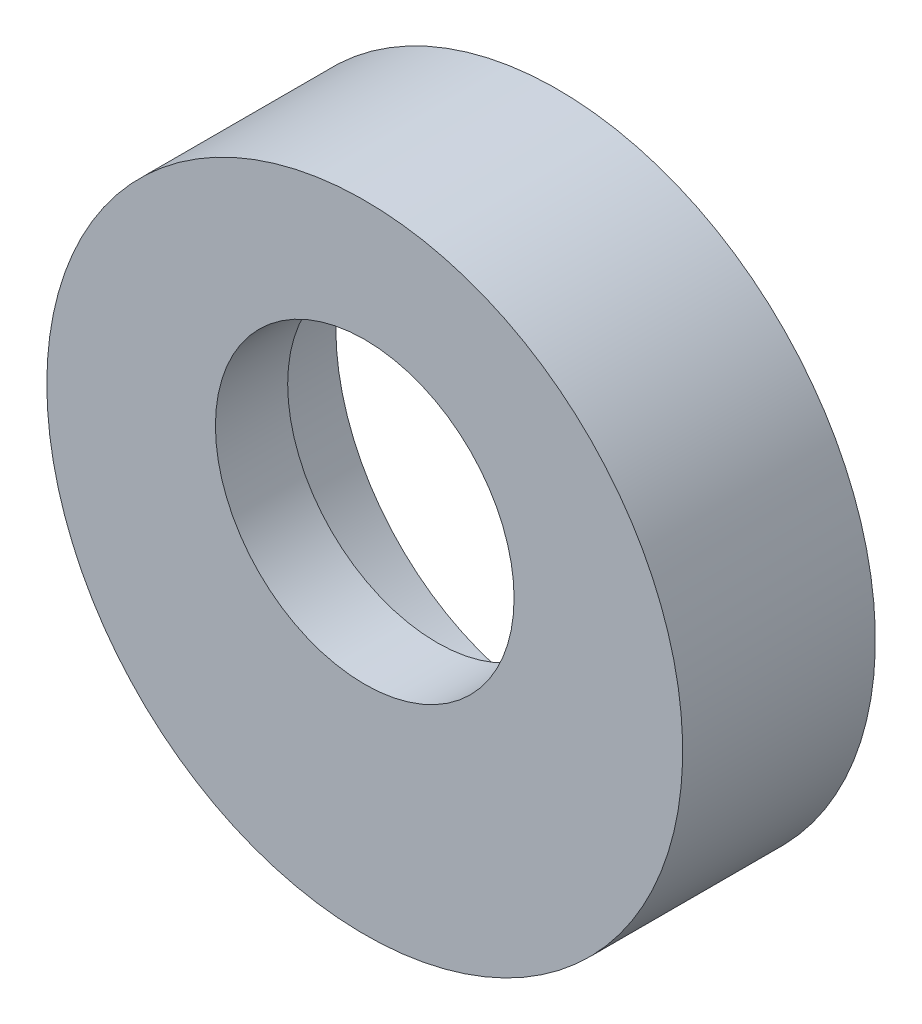
SolidWorks part; units mm, degrees
ref_plane "Front Plane" through (0, 0, 0) normal (0, 0, 1) x (1, 0, 0)
ref_plane "Top Plane" through (0, 0, 0) normal (0, 1, 0) x (1, 0, 0)
ref_plane "Right Plane" through (0, 0, 0) normal (1, 0, 0) x (0, 0, -1)
ref_axis "Axis1" through (0, 0, -55.9602) along (0, 0, 1)
sketch "Sketch2" plane through (0, 0, 0) normal (0, 1, 0) x (1, 0, 0)
  line L0 (-6.6, 4) -> (-6.6, 0)
  line L1 (-44.2539, 0) -> (44.2539, 0) construction
  line L2 (-6.6, 0) -> (0, 0)
  line L3 (0, 0) -> (0, 1.5)
  line L4 (0, -44.7868) -> (0, 44.7868) construction
  line L5 (0, 1.5) -> (-4.6, 1.5)
  line L6 (-4.6, 1.5) -> (-4.6, 4)
  line L7 (-4.6, 4) -> (-6.6, 4)
  dimension "D1" = 2.5
  dimension "D2" = 2
  dimension "D3" = 1.5
  dimension "D4" = 4.6
revolve "Revolve1" add sketch "Sketch2" angle 360 about axis through (0, 0, -55.9602) along (0, 0, 1)
sketch "Sketch3" plane through (0, 0, 0) normal (0, 0, 1) x (1, 0, 0)
  line L0 (0, -44.7868) -> (0, 44.7868) construction
  line L1 (55, 0) -> (-55, 0) construction
  circle A0 centre (0, 1) radius 3.1
  dimension "D1" = 6.2
  dimension "D2" = 1
extrude "Cut-Extrude1" cut sketch "Sketch3" against normal through all
